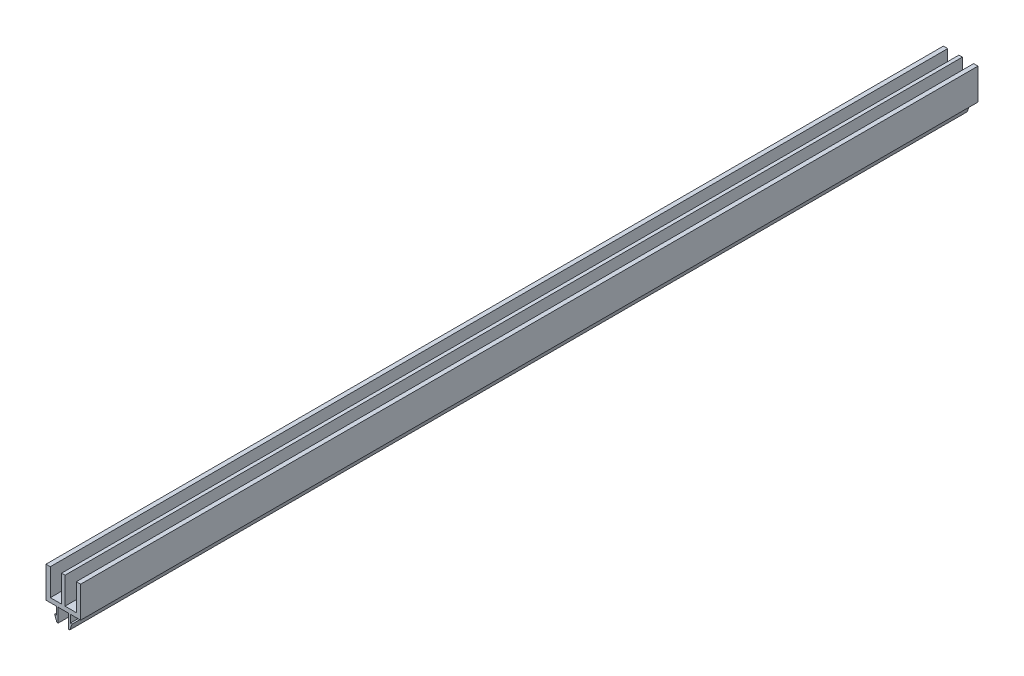
SolidWorks part; units mm, degrees
ref_plane "Plan de face" through (0, 0, 0) normal (0, 0, 1) x (1, 0, 0)
ref_plane "Plan de dessus" through (0, 0, 0) normal (0, 1, 0) x (1, 0, 0)
ref_plane "Plan de droite" through (0, 0, 0) normal (1, 0, 0) x (0, 0, -1)
ref_plane "Plan1" through (0, 0, 50) normal (0, 0, 1) x (1, 0, 0)
sketch "Esquisse1" plane through (0, 0, 50) normal (0, 0, 1) x (1, 0, 0)
  line L0 (-1, 2.5) -> (-7.5, 2.5)
  line L1 (-7.5, 2.5) -> (-7.5, 18)
  line L2 (-7.5, 18) -> (-10, 18)
  line L3 (-10, 18) -> (-10, 0)
  line L4 (-10, 0) -> (-4, 0)
  line L5 (-4, 0) -> (-4, -4.5)
  line L6 (-4, -4.5) -> (-5, -4.5)
  line L7 (-5, -4.5) -> (-3.75, -8)
  line L8 (-3.75, -8) -> (-3, -8)
  line L9 (-3, -8) -> (-3, 0)
  line L10 (-3, 0) -> (3, 0)
  line L11 (3, 0) -> (3, -8)
  line L12 (3, -8) -> (3.75, -8)
  line L13 (3.75, -8) -> (5, -4.5)
  line L14 (5, -4.5) -> (4, -4.5)
  line L15 (4, -4.5) -> (4, 0)
  line L16 (4, 0) -> (10, 0)
  line L17 (10, 0) -> (10, 18)
  line L18 (10, 18) -> (7.5, 18)
  line L19 (7.5, 18) -> (7.5, 2.5)
  line L20 (7.5, 2.5) -> (1, 2.5)
  line L21 (1, 2.5) -> (1, 18)
  line L22 (1, 18) -> (-1, 18)
  line L23 (-1, 18) -> (-1, 2.5)
extrude "Boss.-Extru.1" add sketch "Esquisse1" against normal blind 518
